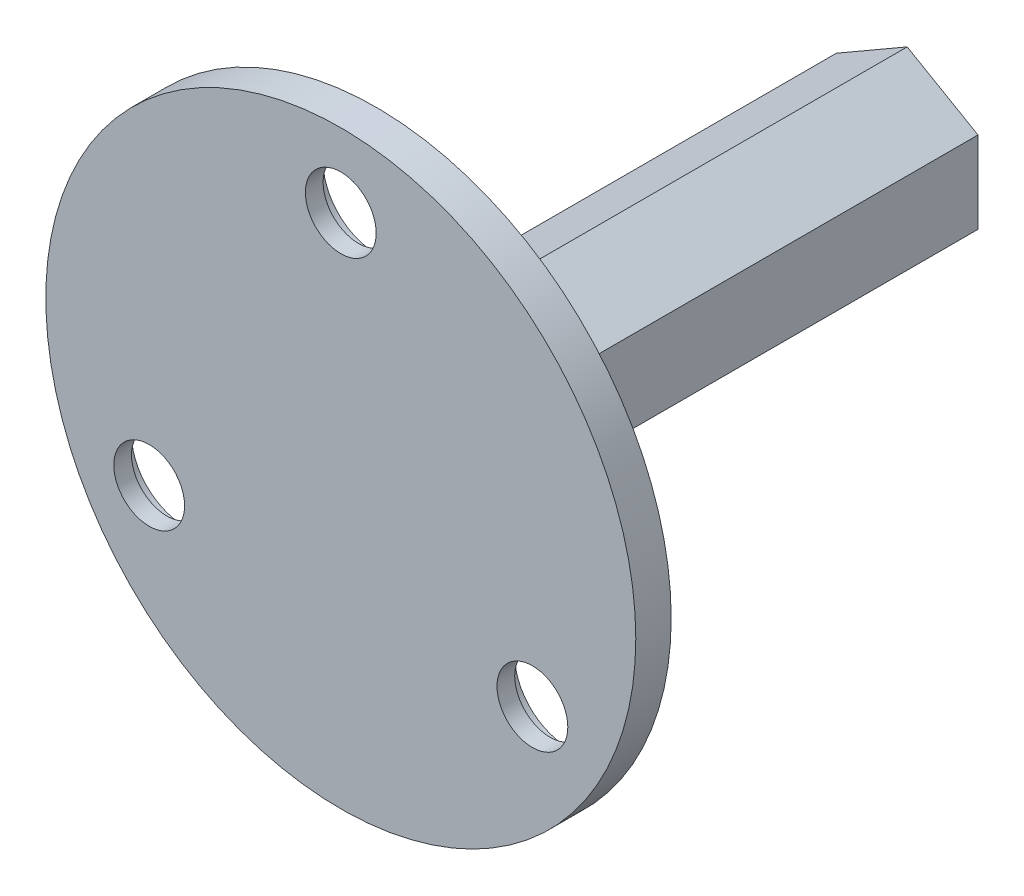
SolidWorks part; units mm, degrees
ref_plane "Front Plane" through (0, 0, 0) normal (0, 0, 1) x (1, 0, 0)
ref_plane "Top Plane" through (0, 0, 0) normal (0, 1, 0) x (1, 0, 0)
ref_plane "Right Plane" through (0, 0, 0) normal (1, 0, 0) x (0, 0, -1)
sketch "Sketch1" plane through (0, 0, 0) normal (0, 0, 1) x (1, 0, 0)
  line L0 (0, 0) -> (0, 18.75) construction
  line L1 (0, 0) -> (0, 18.75) construction
  circle A1 centre (0, 0) radius 25
  circle A2 centre (0, 18.75) radius 3
  circle A3 centre (16.238, -9.375) radius 3
  circle A4 centre (-16.238, -9.375) radius 3
  dimension "D3" = 50
  dimension "D4" = 6
  dimension "D6" = 18.75
  dimension "D5" = 3
extrude "Boss-Extrude1" add sketch "Sketch1" along normal blind 3
sketch "Sketch2" plane through (0, 0, 0) normal (0, 0, -1) x (-1, 0, 0)
  circle A0 centre (0, 0) radius 7.5
  dimension "D1" = 15
extrude "Boss-Extrude2" add sketch "Sketch2" along normal blind 10
sketch "Sketch3" plane through (0, 0, -10) normal (0, 0, -1) x (-1, 0, 0)
  line L1 (0, -6.9282) -> (6, -3.4641)
  line L2 (6, -3.4641) -> (6, 3.4641)
  line L3 (6, 3.4641) -> (0, 6.9282)
  line L4 (0, 6.9282) -> (-6, 3.4641)
  line L5 (-6, 3.4641) -> (-6, -3.4641)
  line L6 (-6, -3.4641) -> (0, -6.9282)
  circle A0 centre (0, 0) radius 6 construction
  dimension "D1" = 12
extrude "Boss-Extrude3" add sketch "Sketch3" along normal blind 35
sketch "Sketch4" plane through (0, 0, -45) normal (0, 0, -1) x (-1, 0, 0)
  circle A0 centre (0, 0) radius 1.25
  dimension "D1" = 2.5
extrude "Cut-Extrude1" cut sketch "Sketch4" against normal blind 10
sketch "Sketch5" plane through (0, 0, 0) normal (0, 0, -1) x (-1, 0, 0)
  circle A0 centre (0, 0) radius 11
  circle A1 centre (0, 0) radius 12.5
  dimension "D1" = 1.5
  dimension "D2" = 25
extrude "Boss-Extrude4" add sketch "Sketch5" along normal blind 0.5
sketch "Sketch6" plane through (0, 0, 0) normal (0, 0, -1) x (-1, 0, 0)
  circle A0 centre (0, 18.75) radius 4.5
  circle A1 centre (16.238, -9.375) radius 4.5
  circle A2 centre (-16.238, -9.375) radius 4.5
  dimension "D1" = 9
extrude "Cut-Extrude2" cut sketch "Sketch6" against normal blind 1.5
